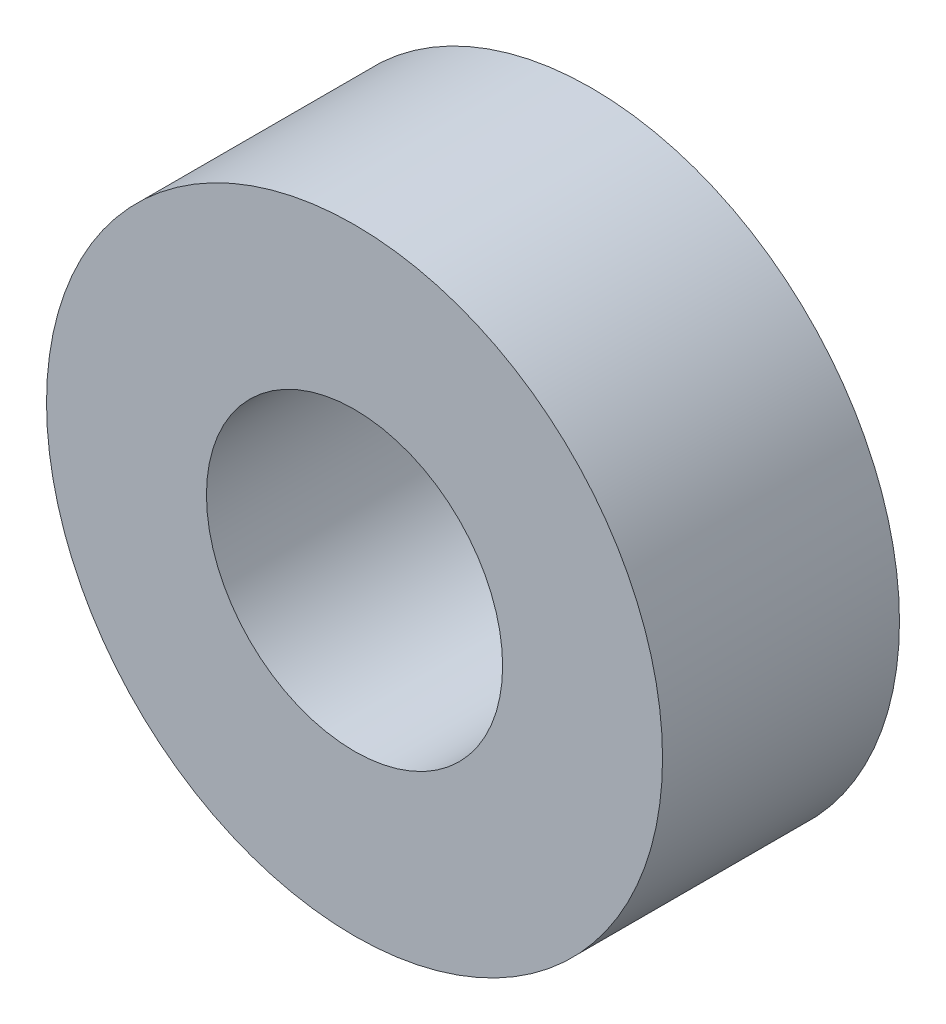
SolidWorks part; units mm, degrees
other "Objet de détail2"
ref_plane "Plan de face" through (0, 0, 0) normal (0, 0, 1) x (1, 0, 0)
ref_plane "Plan de dessus" through (0, 0, 0) normal (0, 1, 0) x (1, 0, 0)
ref_plane "Plan de droite" through (0, 0, 0) normal (1, 0, 0) x (0, 0, -1)
sketch "Esquisse1" plane through (0, 0, 0) normal (0, 0, 1) x (1, 0, 0)
  circle A0 centre (0, 0) radius 6.25
  circle A1 centre (0, 0) radius 13
  dimension "D1" = 12.5
  dimension "D2" = 26
extrude "Boss.-Extru.1" add sketch "Esquisse1" along normal blind 10
